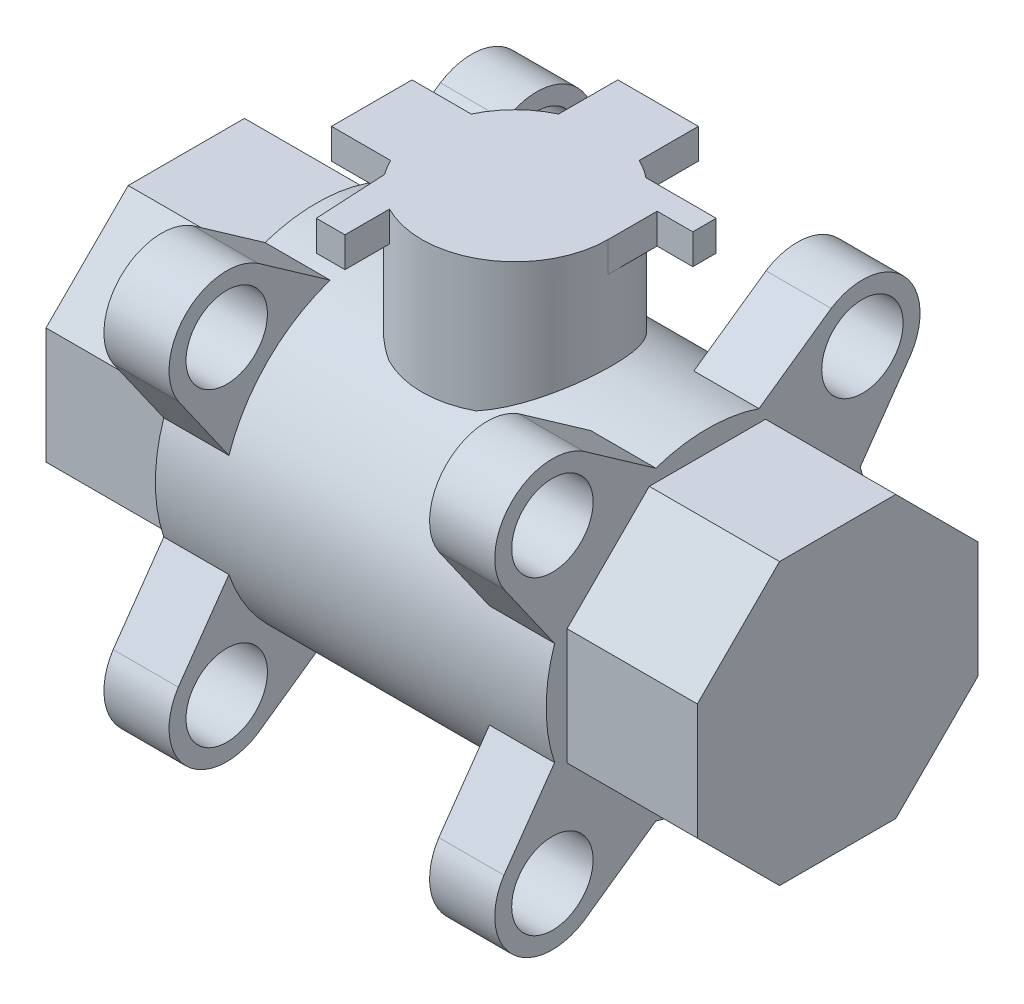
SolidWorks part; units mm, degrees
ref_plane "Front Plane" through (0, 0, 0) normal (0, 0, 1) x (1, 0, 0)
ref_plane "Top Plane" through (0, 0, 0) normal (0, 1, 0) x (1, 0, 0)
ref_plane "Right Plane" through (0, 0, 0) normal (1, 0, 0) x (0, 0, -1)
sketch "Sketch1" plane through (0, 0, 0) normal (1, 0, 0) x (0, 0, -1)
  line L0 (0, 0) -> (0, 26.4768) construction
  line L1 (0, 0) -> (0, -33.4304) construction
  line L2 (-12.3067, 12.3067) -> (-19.0868, 19.0868) construction
  line L3 (-19.8347, 12.0655) -> (-14.8966, 5.0291)
  line L4 (-20.0742, 0) -> (0, 0) construction
  line L5 (0, 0) -> (30.2419, 0) construction
  line L6 (19.8347, 12.0655) -> (14.8966, 5.0291)
  line L7 (12.0655, 19.8347) -> (5.0291, 14.8966)
  line L8 (19.8347, -12.0655) -> (14.8966, -5.0291)
  line L9 (12.0655, -19.8347) -> (5.0291, -14.8966)
  line L10 (-12.0655, 19.8347) -> (-5.0291, 14.8966)
  line L11 (-12.0655, -19.8347) -> (-5.0291, -14.8966)
  line L12 (-19.8347, -12.0655) -> (-14.8966, -5.0291)
  circle A0 centre (-15.113, 15.113) radius 3.9688
  arc A1 (-14.8966, -5.0291) -> (-14.8966, 5.0291) centre (0, 0) cw
  arc A2 (-12.0655, 19.8347) -> (-19.8347, 12.0655) centre (-15.113, 15.113) ccw
  arc A3 (5.0291, 14.8966) -> (-5.0291, 14.8966) centre (0, 0) ccw
  arc A4 (14.8966, -5.0291) -> (14.8966, 5.0291) centre (0, 0) ccw
  circle A5 centre (15.113, 15.113) radius 3.9688
  arc A6 (12.0655, 19.8347) -> (19.8347, 12.0655) centre (15.113, 15.113) cw
  circle A7 centre (15.113, -15.113) radius 3.9688
  arc A8 (12.0655, -19.8347) -> (19.8347, -12.0655) centre (15.113, -15.113) ccw
  arc A9 (5.0291, -14.8966) -> (-5.0291, -14.8966) centre (0, 0) cw
  circle A10 centre (-15.113, -15.113) radius 3.9688
  arc A11 (-12.0655, -19.8347) -> (-19.8347, -12.0655) centre (-15.113, -15.113) cw
  dimension "D3" = 7.9375
  dimension "D4" = 15.7226
  dimension "D5" = 11.2395
  dimension "D1" = 15.113
  dimension "D2" = 15.113
  dimension "D6" = 14.8966
  dimension "D7" = 4.9381
extrude "Boss-Extrude2" add sketch "Sketch1" along normal blind 6.35
sketch "Sketch2" plane through (0, 0, 0) normal (-1, 0, 0) x (0, 0, 1)
  line L0 (0, 0) -> (13.681, 0) construction
  line L1 (0, 0) -> (-13.681, 0) construction
  line L2 (0, 0) -> (0, 17.7652) construction
  line L3 (13.681, 5.6669) -> (13.681, -5.6669)
  line L4 (13.681, -5.6669) -> (5.6669, -13.681)
  line L5 (-5.6669, -13.681) -> (5.6669, -13.681)
  line L6 (-5.6669, -13.681) -> (-13.681, -5.6669)
  line L9 (13.681, 5.6669) -> (5.6669, 13.681)
  line L10 (-5.6669, 13.681) -> (5.6669, 13.681)
  line L11 (-5.6669, 13.681) -> (-13.681, 5.6669)
  line L12 (-13.681, 5.6669) -> (-13.681, -5.6669)
  point P15 (0, 0)
  dimension "D1" = 11.3337
  dimension "D2" = 13.681
  dimension "D3" = 13.681
  dimension "D4" = 45
  dimension "D5" = 11.3337
  dimension "D6" = 5.6669
extrude "Boss-Extrude3" add sketch "Sketch2" along normal blind 12.7
sketch "Sketch3" plane through (6.35, 0, 0) normal (1, 0, 0) x (0, 0, -1)
  circle A0 centre (0, 0) radius 15.7226
  dimension "D1" = 31.4452
extrude "Boss-Extrude4" add sketch "Sketch3" along normal blind 25.4
sketch "Sketch4" plane through (31.75, 0, 0) normal (1, 0, 0) x (0, 0, -1)
  line L0 (0, 0) -> (0, 32.1291) construction
  line L1 (0, 0) -> (0, -27.7781) construction
  line L2 (-12.3067, 12.3067) -> (-19.0868, 19.0868) construction
  line L3 (-19.8347, 12.0655) -> (-14.8966, 5.0291)
  line L4 (-20.0742, 0) -> (0, 0) construction
  line L5 (0, 0) -> (30.2419, 0) construction
  line L6 (19.8347, 12.0655) -> (14.8966, 5.0291)
  line L7 (12.0655, 19.8347) -> (5.0291, 14.8966)
  line L8 (19.8347, -12.0655) -> (14.8966, -5.0291)
  line L9 (12.0655, -19.8347) -> (5.0291, -14.8966)
  line L10 (-12.0655, 19.8347) -> (-5.0291, 14.8966)
  line L11 (-12.0655, -19.8347) -> (-5.0291, -14.8966)
  line L12 (-19.8347, -12.0655) -> (-14.8966, -5.0291)
  circle A0 centre (-15.113, 15.113) radius 3.9688
  arc A1 (-14.8966, -5.0291) -> (-14.8966, 5.0291) centre (0, 0) cw
  arc A2 (-12.0655, 19.8347) -> (-19.8347, 12.0655) centre (-15.113, 15.113) ccw
  arc A3 (5.0291, 14.8966) -> (-5.0291, 14.8966) centre (0, 0) ccw
  arc A4 (14.8966, -5.0291) -> (14.8966, 5.0291) centre (0, 0) ccw
  circle A5 centre (15.113, 15.113) radius 3.9688
  arc A6 (12.0655, 19.8347) -> (19.8347, 12.0655) centre (15.113, 15.113) cw
  circle A7 centre (15.113, -15.113) radius 3.9688
  arc A8 (12.0655, -19.8347) -> (19.8347, -12.0655) centre (15.113, -15.113) ccw
  arc A9 (5.0291, -14.8966) -> (-5.0291, -14.8966) centre (0, 0) cw
  circle A10 centre (-15.113, -15.113) radius 3.9688
  arc A11 (-12.0655, -19.8347) -> (-19.8347, -12.0655) centre (-15.113, -15.113) cw
  point P31 (0, 0)
  dimension "D1" = 7.9375
  dimension "D2" = 11.2395
  dimension "D5" = 15.7226
  dimension "D3" = 15.113
  dimension "D4" = 15.113
  dimension "D6" = 14.8966
  dimension "D7" = 4.9381
  dimension "D8" = 0
  dimension "D9" = 0
extrude "Boss-Extrude5" add sketch "Sketch4" along normal blind 6.35
sketch "Sketch5" plane through (38.1, 0, 0) normal (1, 0, 0) x (0, 0, -1)
  line L0 (0, 0) -> (13.681, 0) construction
  line L1 (0, 0) -> (-13.681, 0) construction
  line L2 (0, 0) -> (0, 17.7652) construction
  line L3 (13.681, 5.6669) -> (13.681, -5.6669)
  line L4 (13.681, -5.6669) -> (5.6669, -13.681)
  line L5 (-5.6669, -13.681) -> (5.6669, -13.681)
  line L6 (-5.6669, -13.681) -> (-13.681, -5.6669)
  line L7 (13.681, 5.6669) -> (5.6669, 13.681)
  line L8 (-5.6669, 13.681) -> (5.6669, 13.681)
  line L9 (-5.6669, 13.681) -> (-13.681, 5.6669)
  line L10 (-13.681, 5.6669) -> (-13.681, -5.6669)
  point P12 (2.6974, 0.6715)
  dimension "D1" = 11.3337
  dimension "D2" = 13.681
  dimension "D3" = 13.681
  dimension "D4" = 45
  dimension "D5" = 11.3337
  dimension "D6" = 5.6669
  dimension "D7" = 0
  dimension "D8" = 0
extrude "Boss-Extrude6" add sketch "Sketch5" along normal blind 12.7
sketch "Sketch6" plane through (0, 13.681, 0) normal (0, 1, 0) x (1, 0, 0)
  line L0 (-12.7, 0) -> (50.8, 0.568) construction
  line L1 (-12.7, -5.6669) -> (-12.7, 5.6669) construction
  line L2 (50.8, 5.6669) -> (50.8, -5.6669) construction
  line L3 (19.05, 0.284) -> (19.05, 15.7226) construction
  line L4 (38.1, 15.7226) -> (0, 15.7226) construction
  circle A0 centre (19.05, 0.284) radius 9.0805
  dimension "D1" = 18.161
  dimension "D2" = 15.4386
extrude "Boss-Extrude8" add sketch "Sketch6" along normal blind 12.8778
sketch "Sketch8" plane through (0, 26.5588, 0) normal (0, 1, 0) x (1, 0, 0)
  line L0 (15.1257, 6.1641) -> (15.1257, 14.2413)
  line L1 (13.1699, -3.6403) -> (13.1699, 4.2083)
  line L2 (15.1257, 14.2413) -> (22.9743, 14.2413)
  line L3 (22.9743, 14.2413) -> (22.9743, 6.1641)
  line L4 (22.9743, 6.1641) -> (15.1257, 6.1641)
  line L5 (5.0927, -3.6403) -> (13.1699, -3.6403)
  line L6 (12.6291, 6.7049) -> (19.05, 0.284) construction
  line L7 (5.0927, 4.2083) -> (5.0927, -3.6403)
  line L8 (13.1699, 4.2083) -> (5.0927, 4.2083)
  circle A0 centre (19.05, 0.284) radius 9.0805 construction
  dimension "D1" = 7.8486
  dimension "D2" = 6.4209
  dimension "D3" = 8.0772
  dimension "D4" = 5.8801
  dimension "D5" = 3.9243
extrude "Boss-Extrude9" add sketch "Sketch8" against normal blind 2.9464
sketch "Sketch10" plane through (0, 26.5588, 0) normal (0, 1, 0) x (1, 0, 0)
  line L0 (24.7523, 7.3508) -> (31.6103, 7.3508)
  line L1 (31.6103, 7.3508) -> (31.6103, 5.0648)
  line L2 (28.1305, 0.284) -> (28.1305, 5.0648)
  line L3 (28.1305, 5.0648) -> (31.6103, 5.0648)
  line L6 (11.7439, -5.1083) -> (12.1125, -12.1405)
  line L7 (12.1125, -12.1405) -> (14.9065, -12.1405)
  line L8 (14.9065, -12.1405) -> (14.9065, -7.796)
  arc A0 (14.9065, -7.796) -> (28.1305, 0.284) centre (19.05, 0.284) ccw
  arc A1 (24.7523, 7.3508) -> (11.7439, -5.1083) centre (19.05, 0.284) ccw
  point P3 (0, 0)
  point P8 (0, 0)
  point P10 (11.4756, -3.5593)
  point P14 (0, 0)
  point P16 (0, 0)
  point P17 (0, 0)
  point P18 (0, 0)
  point P19 (14.1017, -3.5664)
  dimension "D1" = 18.161
  dimension "D2" = 6.858
  dimension "D3" = 93
  dimension "D4" = 2.286
  dimension "D5" = 3.4798
  dimension "D6" = 4.3445
  dimension "D7" = 5.3923
  dimension "D8" = 2.794
extrude "Boss-Extrude10" add sketch "Sketch10" against normal blind 2.9464
